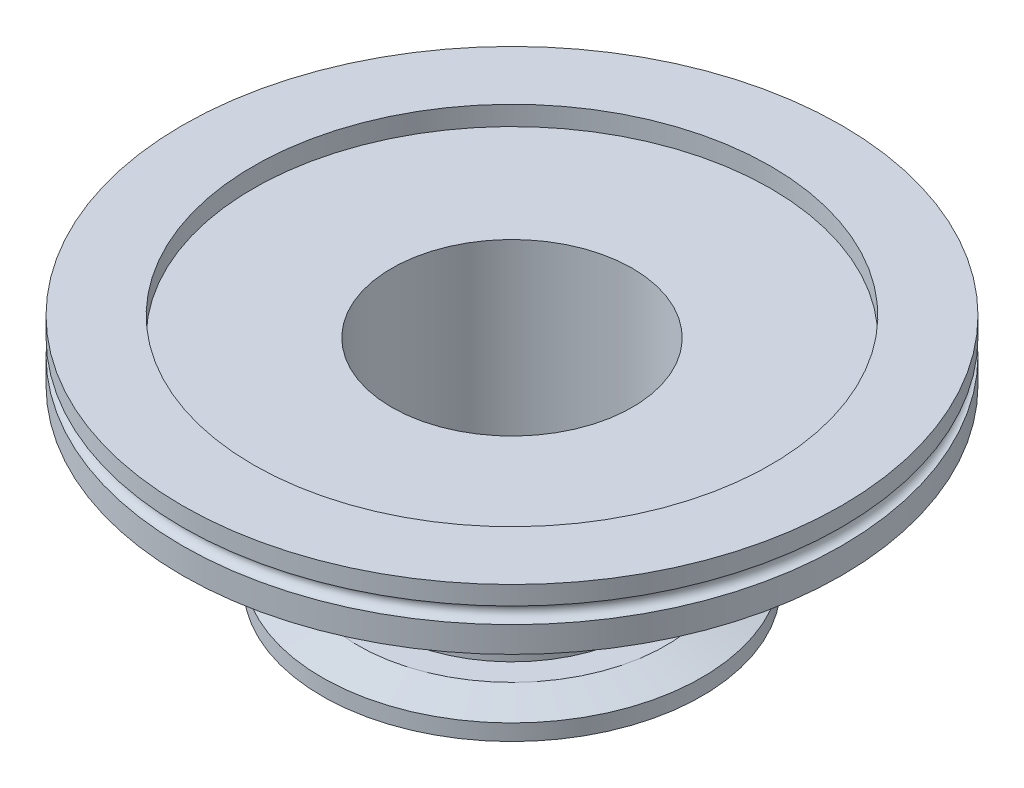
SolidWorks part; units mm, degrees
material "AISI 304"
ref_plane "Front Plane" through (0, 0, 0) normal (0, 0, 1) x (1, 0, 0)
ref_plane "Top Plane" through (0, 0, 0) normal (0, 1, 0) x (1, 0, 0)
ref_plane "Right Plane" through (0, 0, 0) normal (1, 0, 0) x (0, 0, -1)
sketch "Sketch1" plane through (0, 0, 0) normal (0, 0, 1) x (1, 0, 0)
  line L0 (-65, 5.969) -> (-65, -5.969)
  line L1 (-65, -5.969) -> (0, -5.969)
  line L6 (0, -5.969) -> (0, 0) construction
  line L7 (0, 0) -> (-65, 0) construction
  line L12 (-65, 5.969) -> (0, 5.969)
  line L13 (0, 5.969) -> (0, -5.969)
  dimension "D" = 11.938
  dimension "LF_Flange_Diam" = 130
revolve "Blank" add sketch "Sketch1" angle 360 about L13
sketch "Sketch7" plane through (0, 0, 0) normal (0, 0, 1) x (1, 0, 0)
  line L0 (-23.749, -5.969) -> (-23.749, 2.159)
  line L1 (65, 5.969) -> (-65, 5.969) construction
  line L2 (-23.749, 2.159) -> (-51.03, 2.159)
  line L3 (-51.03, 2.159) -> (-51.03, 5.969)
  line L4 (-51.03, 5.969) -> (0, 5.969)
  line L5 (0, 5.969) -> (0, -5.969)
  line L6 (0, -5.969) -> (-23.749, -5.969)
  line L7 (65, 5.969) -> (-65, 5.969) construction
  line L8 (0, 5.969) -> (0, 10.8934) construction
  line L9 (-65, -5.969) -> (65, -5.969) construction
  line L10 (-65, 5.969) -> (-65, -5.969) construction
  dimension "D1" = 13.97
  dimension "Tube ID Bottom" = 47.498
  dimension "Flange to Bore" = 3.81
revolve "Single Side Bore" cut sketch "Sketch7" angle 360 about L8
sketch "Sketch9" plane through (0, 0, 0) normal (0, 0, 1) x (1, 0, 0)
  line L0 (0, 5.969) -> (0, -35.4838) construction
  line L1 (30.3554, -35.251) -> (23.749, -35.251)
  line L2 (26.1239, -40.331) -> (37.465, -40.331)
  line L3 (37.465, -40.331) -> (37.465, -37.156)
  line L4 (37.465, -37.156) -> (30.3554, -35.251)
  line L5 (26.1239, -40.331) -> (26.1239, -37.7148)
  line L6 (23.749, -35.251) -> (23.749, -37.7148)
  line L7 (23.749, -37.7148) -> (26.1239, -37.7148)
  line L9 (0, -35.251) -> (0, -40.331) construction
  line L10 (65, 5.969) -> (-65, 5.969) construction
  dimension "D1" = 105
  dimension "Height" = 46.3
  dimension "D2" = 2.6162
  dimension "D3" = 3.175
  dimension "D4" = 74.93
  dimension "D5" = 52.2478
  dimension "D6" = 5.08
  dimension "D7" = 47.498
revolve "KF Flange" add sketch "Sketch9" angle 360 about L0
sketch "Sketch8" plane through (0, 0, 0) normal (0, 0, 1) x (1, 0, 0)
  line L0 (-23.749, 2.159) -> (-23.749, -13.081)
  line L1 (-23.749, -13.081) -> (-23.749, -22.4748)
  line L2 (-25.4, -22.4748) -> (-23.749, -22.4748) construction
  line L3 (-25.4, -13.081) -> (-23.749, -13.081) construction
  line L4 (51.03, 2.159) -> (-51.03, 2.159) construction
  line L5 (-26.1239, -37.7148) -> (26.1239, -37.7148) construction
  line L6 (-23.749, -37.7148) -> (-25.4, -37.7148)
  line L7 (-23.749, -37.7148) -> (-23.749, -22.4748)
  line L8 (-25.4, -37.7148) -> (-25.4, -22.4748)
  line L9 (-23.749, 2.159) -> (-23.749, -5.969) construction
  line L10 (-25.4, -22.4748) -> (-25.4, -13.081)
  line L11 (-25.4, -13.081) -> (-25.4, 2.159)
  line L13 (-25.4, 2.159) -> (-23.749, 2.159)
  line L14 (0, 0) -> (0, -25.3856) construction
  dimension "Top Tube ID" = 47.498
  dimension "Top Tube OD" = 50.8
  dimension "Bottom to Conical" = 19.05
revolve "Revolve1" add sketch "Sketch8" angle 360 about L14
sketch "Sketch13" plane through (0, 0, 0) normal (0, 0, 1) x (1, 0, 0)
  line L0 (-65, -5.969) -> (65, -5.969) construction
  line L1 (-62.46, -5.969) -> (-57.38, -5.969)
  line L2 (-62.46, -5.969) -> (-62.46, -3.937)
  line L3 (-62.46, -3.937) -> (-57.38, -3.937)
  line L4 (-57.38, -5.969) -> (-57.38, -3.937)
  line L5 (0, 0) -> (0, -3.0965) construction
  line L6 (-65, 5.969) -> (-65, -5.969) construction
  dimension "D1" = 2.032
  dimension "D2" = 5.08
  dimension "D3" = 2.54
revolve "Cut-Revolve2" cut sketch "Sketch13" angle 360 about L5
sketch "Sketch15" plane through (0, 0, 0) normal (0, 0, 1) x (1, 0, 0)
  line L0 (-65, 5.969) -> (-65, -5.969) construction
  line L1 (0, 0) -> (0, -5.0977) construction
  line L2 (-65, 2.286) -> (-65, -0.889)
  arc A0 (-65, 2.286) -> (-65, -0.889) centre (-65, 0.6985) cw
  dimension "D1" = 3.175
  dimension "D2" = 3.683
revolve "Cut-Revolve3" cut sketch "Sketch15" angle 360 about L1
ref_plane "Plane1" through (0, -42.236, 0) normal (0, -1, 0) x (-1, 0, 0)
ref_plane "Plane2" through (0, 7.969, 0) normal (0, 1, 0) x (1, 0, 0)
equation "\"Holes@Thru Hole Pattern\"=\"bolt holes\""
equation "\"D7@Sketch9\"=\"Top Tube ID@Sketch8\""
